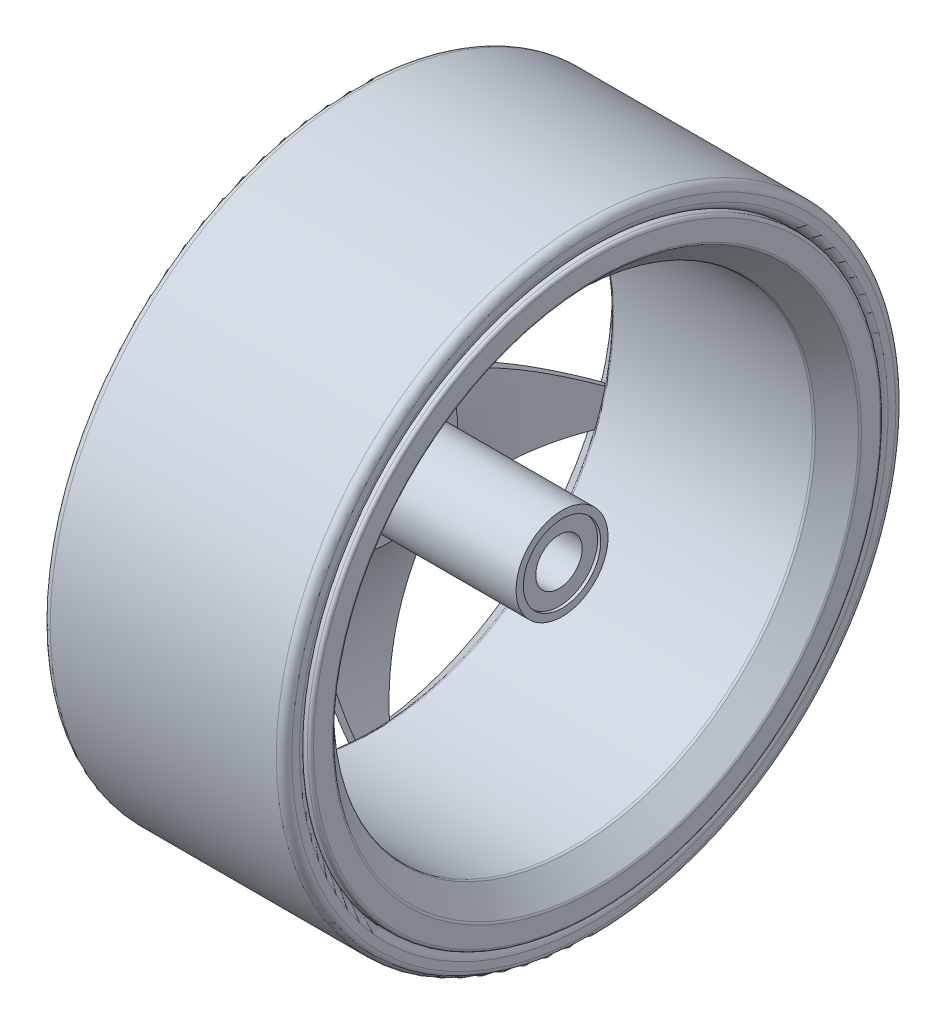
SolidWorks part; units mm, degrees
ref_plane "Front Plane" through (0, 0, 0) normal (0, 0, 1) x (1, 0, 0)
ref_plane "Top Plane" through (0, 0, 0) normal (0, 1, 0) x (1, 0, 0)
ref_plane "Right Plane" through (0, 0, 0) normal (1, 0, 0) x (0, 0, -1)
sketch "Sketch1" plane through (0, 0, 0) normal (0, 0, 1) x (1, 0, 0)
  line L0 (-5, 0) -> (5, 0) construction
  line L1 (-6.5, 15.5) -> (6.5, 15.5)
  line L2 (-8, 18.5) -> (-6.5, 18.5)
  line L3 (-5, 16.5) -> (5, 16.5)
  line L4 (-8, 18.5) -> (-8, 17)
  line L5 (8, 18.5) -> (8, 17)
  line L6 (-5, 16.5) -> (-6.5, 18.5)
  line L7 (-8, 17) -> (-6.5, 15.5)
  line L8 (6.5, 18.5) -> (8, 18.5)
  line L9 (6.5, 15.5) -> (8, 17)
  line L10 (6.5, 18.5) -> (5, 16.5)
  point P2 (0, 0)
  point P3 (0, 0)
  point P7 (0, 15.5)
  point P12 (0, 16.5)
  dimension "D1" = 10
  dimension "D2" = 6.5
  dimension "D3" = 15.5
  dimension "D4" = 5
  dimension "D5" = 1
  dimension "D6" = 18.5
  dimension "D7" = 1.5
revolve "Revolve1" add sketch "Sketch1" angle 360 about L0
fillet "Fillet1" radius 0.2 10 edges at (-8, 0, 17) (-8, 0, 18.5) (-6.5, 0, 18.5) (-5, 0, 16.5) (5, 0, 16.5) (6.5, 0, 18.5) (8, 0, 17) (6.5, 0, 15.5) (-6.5, 0, 15.5) (8, 0, 18.5)
sketch "Sketch2" plane through (0, 0, 0) normal (0, 0, 1) x (1, 0, 0)
  line L0 (-6.25, 2.5) -> (-4.75, 2.5)
  line L1 (-5.5, 2.9721) -> (5.75, 2.9721)
  line L2 (-4.75, 2.5) -> (-4.75, 0)
  line L3 (-5, 0) -> (5, 0) construction
  line L4 (-4.75, 0) -> (-4, 0)
  line L5 (-4, 0) -> (-4, 2.5)
  line L6 (-6.25, 2.5) -> (-6.25, 4.5)
  line L7 (-5.5, 2.9721) -> (-5.5, 4.5)
  line L8 (-4, 2.5) -> (5.75, 2.5)
  line L9 (5.75, 2.5) -> (5.75, 2.9721)
  line L10 (0, 0) -> (0, 16.5) construction
  line L11 (-5, 16.5) -> (5, 16.5) construction
  line L12 (-8, 17) -> (-6.5, 15.5) construction
  line L13 (-7.0303, 16.0303) -> (-6.5, 15.5)
  arc A0 (-5.5, 4.5) -> (-6.5, 15.5) centre (7.2782, 11.2071) cw
  arc A1 (-6.25, 4.5) -> (-7.0303, 16.0303) centre (7.2782, 11.2071) cw
  point P4 (0.125, 2.9721)
  dimension "D1" = 12
  dimension "D2" = 1.5
  dimension "D3" = 0.75
  dimension "D4" = 2.5
  dimension "D5" = 2
  dimension "D6" = 0.75
  dimension "D7" = 1.25
  dimension "D8" = 11.25
  dimension "D9" = 0.75
revolve "Revolve2" add sketch "Sketch2" angle 360 about L0
sketch "Sketch4" plane through (0, 0, 0) normal (1, 0, 0) x (0, 0, -1)
  line L0 (0, 0) -> (0, 16.0303) construction
  line L1 (8.6273, 13.5108) -> (1.5, 7.5303)
  line L2 (-8.6273, 13.5108) -> (-1.5, 7.5303)
  line L3 (10.1836, 12.3801) -> (6.6982, 3.7536)
  line L4 (15.5155, -4.0299) -> (7.6253, 0.9004)
  line L5 (14.9211, -5.8595) -> (5.6397, -5.2105)
  line L6 (0.9619, -16.0014) -> (3.2127, -6.9738)
  line L7 (-0.9619, -16.0014) -> (-3.2127, -6.9738)
  line L8 (-14.9211, -5.8595) -> (-5.6397, -5.2105)
  line L9 (-15.5155, -4.0299) -> (-7.6253, 0.9004)
  line L10 (-10.1836, 12.3801) -> (-6.6982, 3.7536)
  circle A0 centre (0, 0) radius 16.0303 construction
  arc A1 (1.5, 7.5303) -> (-1.5, 7.5303) centre (0, 0) ccw
  arc A2 (8.6273, 13.5108) -> (-8.6273, 13.5108) centre (0, 0) ccw
  arc A3 (15.5155, -4.0299) -> (10.1836, 12.3801) centre (0, 0) ccw
  arc A4 (7.6253, 0.9004) -> (6.6982, 3.7536) centre (0, 0) ccw
  arc A5 (0.9619, -16.0014) -> (14.9211, -5.8595) centre (0, 0) ccw
  arc A6 (3.2127, -6.9738) -> (5.6397, -5.2105) centre (0, 0) ccw
  arc A7 (-14.9211, -5.8595) -> (-0.9619, -16.0014) centre (0, 0) ccw
  arc A8 (-5.6397, -5.2105) -> (-3.2127, -6.9738) centre (0, 0) ccw
  arc A9 (-10.1836, 12.3801) -> (-15.5155, -4.0299) centre (0, 0) ccw
  arc A10 (-6.6982, 3.7536) -> (-7.6253, 0.9004) centre (0, 0) ccw
  point P28 (0, 0)
  dimension "D1" = 3
  dimension "D2" = 50
  dimension "D3" = 50
  dimension "D4" = 8.5
  dimension "D5" = 5
extrude "Cut-Extrude1" cut sketch "Sketch4" against normal blind 10 and the other way blind 10
combine bodies "Combine1" operation type add bodies to combine 103 101
sketch "Sketch5" plane through (0, 0, 0) normal (0, 0, 1) x (1, 0, 0)
  line L0 (-7.3, 18.5) -> (-6.5, 18.5)
  line L1 (-6.5, 18.5) -> (-5, 16.5)
  line L2 (-5, 16.5) -> (5, 16.5)
  line L3 (5, 16.5) -> (6.6, 18.5)
  line L4 (6.6, 18.5) -> (7.3, 18.5)
  line L5 (7.8, 19) -> (7.8, 19.5)
  line L6 (7.3, 20) -> (-7.3, 20)
  line L7 (-7.8, 19.5) -> (-7.8, 19)
  line L8 (-5, 0) -> (5, 0) construction
  line L10 (-5, 0) -> (5, 0)
  arc A0 (7.3, 18.5) -> (7.8, 19) centre (7.3, 19) ccw
  arc A1 (-7.3, 18.5) -> (-7.8, 19) centre (-7.3, 19) cw
  arc A2 (7.8, 19.5) -> (7.3, 20) centre (7.3, 19.5) ccw
  arc A3 (-7.3, 20) -> (-7.8, 19.5) centre (-7.3, 19.5) ccw
  point P2 (0, 0)
  point P3 (-6.5, 17.8)
  point P4 (0, 20)
  point P6 (-6.5, 18.5)
  point P8 (-5, 16.5)
  point P10 (5.06, 16.58)
  point P12 (6.6, 18.5)
  point P18 (0, 0)
  point P24 (-5, 16.5)
  point P25 (-4.9723, 17.2953)
  point P26 (5, 16.5)
  point P28 (-5, 16.5)
  point P32 (7.8, 18.5)
  point P35 (-7.8, 18.5)
  point P38 (7.8, 20)
  point P41 (-7.8, 20)
  dimension "D4" = 0.5
  dimension "D1" = 20
  dimension "D2" = 1.5
  dimension "D3" = 1.5
revolve "Revolve3" add sketch "Sketch5" angle 360 about L10
fillet "Fillet32" radius 0.5 2 edges at (-6.25, 0, 2.5) (-4.75, 0, 2.5)
sketch "Sketch6" plane through (5.75, 0, 0) normal (1, 0, 0) x (0, 0, -1)
  circle A0 centre (0, 0) radius 1.5
  circle A1 centre (0, 0) radius 2.5 construction
  circle A2 centre (0, 0) radius 2.5
  dimension "D1" = 3
extrude "Boss-Extrude1" add sketch "Sketch6" against normal blind 10 from offset 0.2 separate body offset against normal yes
